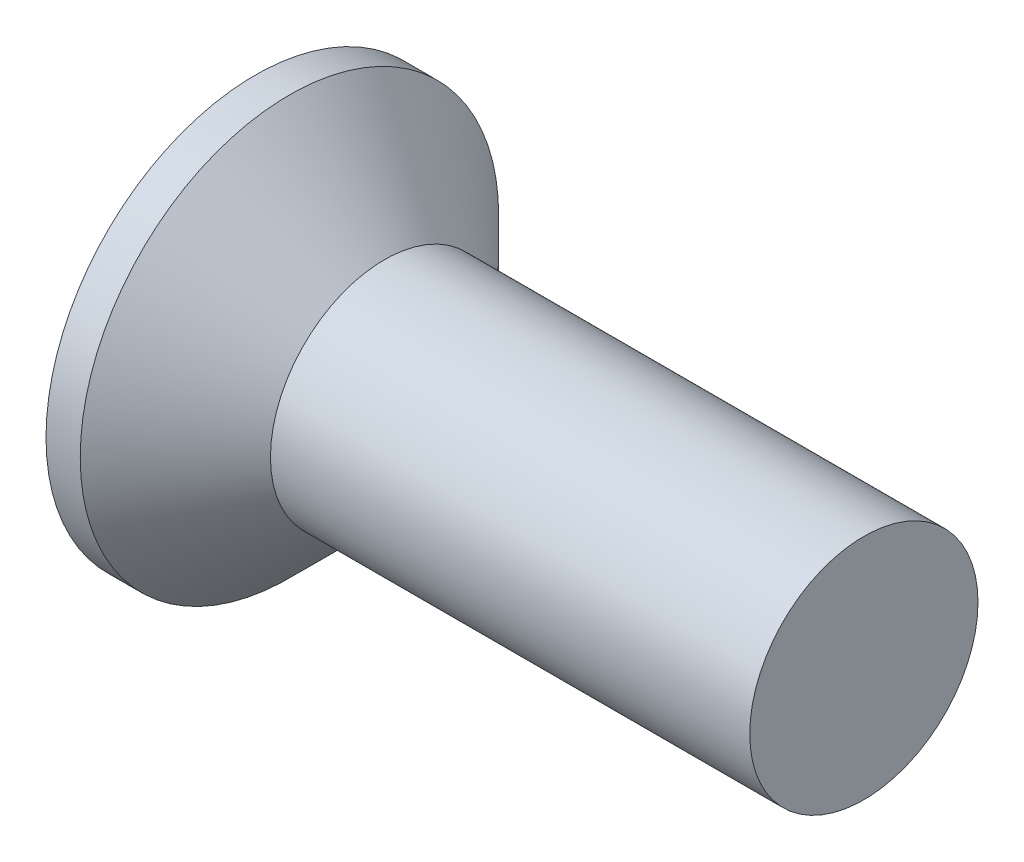
SolidWorks part; units mm, degrees
revolve "Base-Revolve" add sketch "BodySke" angle 360 about L5
sketch "BodySke" plane through (0, 0, 0) normal (0, 0, 1) x (1, 0, 0)
  line L0 (0, 0) -> (0, 2.75)
  line L1 (0, 2.75) -> (0.45, 2.75)
  line L2 (1.7, 1.5) -> (8, 1.5)
  line L3 (8, 1.5) -> (8, 0)
  line L4 (8, 0) -> (0, 0)
  line L5 (-6.35, 0) -> (82.55, 0) construction
  line L6 (1.7, -1.5) -> (8, -1.5) construction
  line L7 (0.45, -2.75) -> (1.7, -1.5) construction
  line L8 (0.45, 2.75) -> (1.7, 1.5)
  line L9 (0, -2.75) -> (0.45, -2.75) construction
  line L10 (2.2, 3.0875) -> (2.2, -6.4375) construction
  line L11 (0, 6.35) -> (0, -3.175) construction
  dimension "Diameter" = 3
  dimension "Length" = 8
  dimension "Head_ht" = 1.7
  dimension "Head_dia" = 5.5
  dimension "Head_ang" = 90
  dimension "D6" = 0.45
  dimension "Advance" = 0.5
  dimension "Thread_nom" = 8
cosmetic thread "ThreadCosmetic" [suppressed] parameters "Thread_length"=5.8, "Thread_minor"=2.439
extrude "Slot" [suppressed] cut sketch "Sketch2" against normal blind 0.9
sketch "Sketch2" plane through (0, 0, 0) normal (-1, 0, 0) x (0, 0, 1)
  line L0 (-2.75, -0.5) -> (2.75, -0.5)
  line L1 (-2.75, -0.5) -> (-2.75, 0.5)
  line L2 (2.75, 0.5) -> (-2.75, 0.5)
  line L3 (2.75, 0.5) -> (2.75, -0.5)
  dimension "Slot_width" = 1
  dimension "D1" = 0.5
  dimension "D2" = 5.5
  dimension "D3" = 2.75
ref_plane "Plane1" through (0, 0, 0) normal (0, 0, 1) x (1, 0, 0)
ref_plane "Plane2" through (0, 0, 0) normal (0, 1, 0) x (1, 0, 0)
ref_plane "Plane3" through (0, 0, 0) normal (1, 0, 0) x (0, 0, -1)
sketch "Sketch3" plane through (0, 0, 0) normal (-1, 0, 0) x (0, 0, 1)
  line L0 (-0.395, 1.55) -> (0.395, 1.55)
  line L1 (0.395, 1.55) -> (0.395, -1.55)
  line L2 (0.395, -1.55) -> (-0.395, -1.55)
  line L3 (-0.395, -1.55) -> (-0.395, 1.55)
  dimension "Cross_dia" = 3.1
  dimension "Cross_width" = 0.79
  dimension "D1" = 1.55
  dimension "D2" = 0.395
ref_plane "Plane4" through (2.08, 0, 0) normal (-1, 0, 0) x (0, 0, 1)
sketch "Sketch4" plane through (2.08, 0, 0) normal (-1, 0, 0) x (0, 0, 1)
  line L0 (-0.1975, 0.1975) -> (0.1975, 0.1975)
  line L3 (0.1975, 0.1975) -> (0.1975, -0.1975)
  line L4 (0.1975, -0.1975) -> (-0.1975, -0.1975)
  line L5 (-0.1975, -0.1975) -> (-0.1975, 0.1975)
  dimension "D2" = 0.395
  dimension "D1" = 0.395
  dimension "D3" = 0.1975
  dimension "D4" = 0.1975
loft "Cross" cut profiles "Sketch3", "Sketch4"
pattern_circular "CirPattern1" count 2 every 90 about axis through (0, 0, 0) along (1, 0, 0) of "Cross"
sketch "ThdSchSke" plane through (0, 0, 0) normal (0, 0, 1) x (1, 0, 0)
  line L0 (2.2, -1.2195) -> (2.0036, -1.5)
  line L1 (2.2, -1.2195) -> (2.3964, -1.5)
  line L2 (2.3964, -1.5) -> (2.3964, -1.875)
  line L3 (-3.175, 0) -> (5.1513, 0) construction
  line L5 (2.3964, -1.875) -> (2.0036, -1.875)
  line L6 (2.0036, -1.875) -> (2.0036, -1.5)
  line L7 (0, 2.75) -> (0, -2.75) construction
  dimension "Diameter" = 3
  dimension "Thread_minor" = 2.439
  dimension "Start" = 2.2
revolve "ThreadSchematic" [suppressed] cut sketch "ThdSchSke" angle 360 about L3
pattern_linear "ThdSchPat" [suppressed]
equation "\"D1@Sketch3\" = \"Cross_dia@Sketch3\" / 2"
equation "\"D2@Sketch3\" = \"Cross_width@Sketch3\" / 2"
equation "\"D1@Sketch4\" = \"Cross_width@Sketch3\" *.5"
equation "\"D2@Sketch4\" = \"D1@Sketch4\""
equation "\"D4@Sketch4\" = \"D2@Sketch4\" / 2"
equation "\"D3@Sketch4\" = \"D1@Sketch4\" / 2"
equation "\"D1@Sketch2\" = \"Slot_width@Sketch2\" / 2"
equation "\"D2@Sketch2\" = \"Head_dia@BodySke\""
equation "\"D3@Sketch2\" = \"D2@Sketch2\" / 2"
equation "\"Thread_length@ThreadCosmetic\" = ((sgn( (\"Length@BodySke\" - \"Advance@BodySke\" - \"Head_ht@BodySke\" ) - \"Thread_nom@BodySke\" )-1)*( (\"Length@BodySke\" - \"Advance@BodySke\" - \"Head_ht@BodySke\" ) - \"Thread_nom@BodySke\" ))/-2+ \"Thread_nom@BodySke\""
equation "\"Thread_minor@ThdSchSke\" = \"Thread_minor@ThreadCosmetic\""
equation "\"Diameter@ThdSchSke\" = \"Diameter@BodySke\""
equation "\"Overcut@ThdSchSke\" = \"Diameter@BodySke\" * 1.25"
equation "\"Start@ThdSchSke\" = 0.000001 + \"Length@BodySke\" - \"Thread_length@ThreadCosmetic\"  '---Countersunk---"
equation "\"Num_threads@ThdSchPat\" = int( \"Thread_length@ThreadCosmetic\" / \"Advance@BodySke\" + 0.999 )  + 1"
equation "\"Advance@ThdSchPat\" = \"Thread_length@ThreadCosmetic\" /  (\"Num_threads@ThdSchPat\" - 1) 'relax it"
